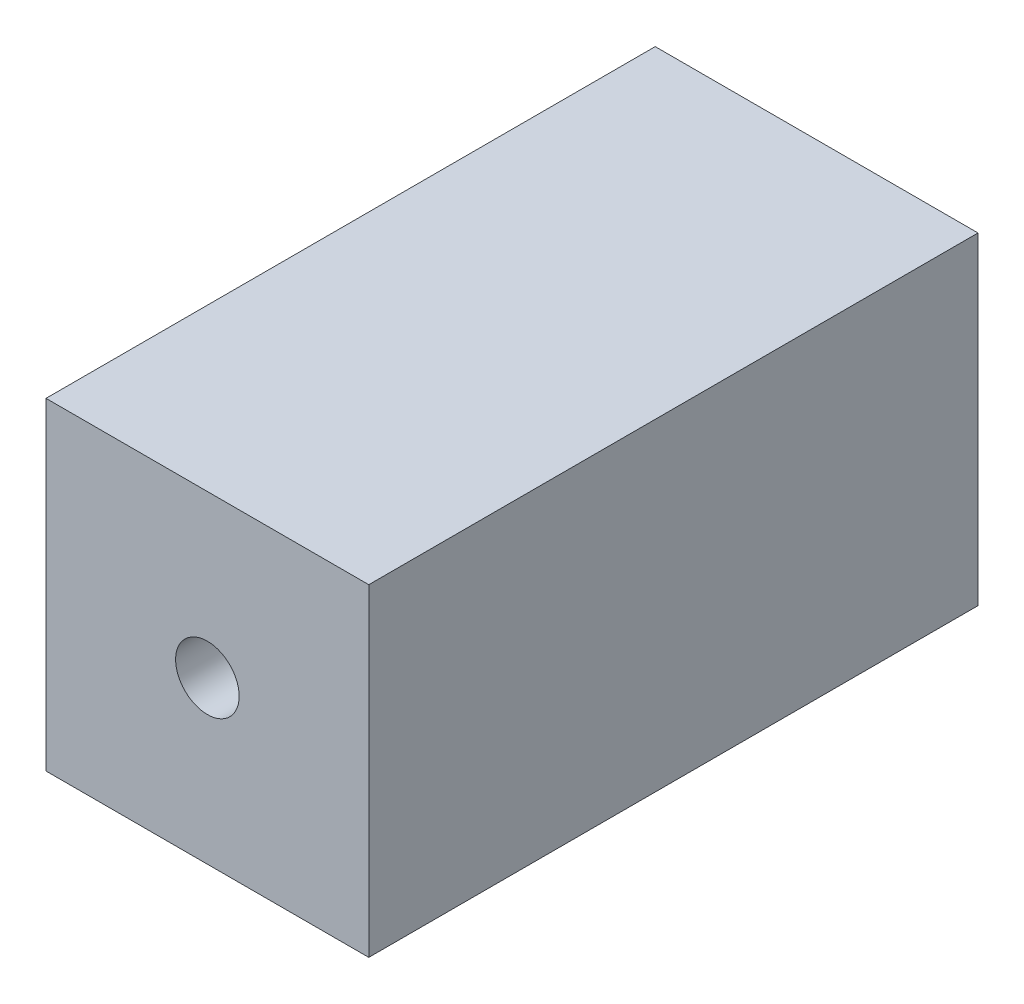
SolidWorks part; units mm, degrees
ref_plane "Front Plane" through (0, 0, 0) normal (0, 0, 1) x (1, 0, 0)
ref_plane "Top Plane" through (0, 0, 0) normal (0, 1, 0) x (1, 0, 0)
ref_plane "Right Plane" through (0, 0, 0) normal (1, 0, 0) x (0, 0, -1)
sketch "Sketch1" plane through (0, 0, 0) normal (0, 0, 1) x (1, 0, 0)
  line L1 (-12.7, -12.7) -> (12.7, -12.7)
  line L2 (-12.7, -12.7) -> (-12.7, 12.7)
  line L3 (-12.7, 12.7) -> (12.7, 12.7)
  line L4 (12.7, -12.7) -> (12.7, 12.7)
  line L5 (-12.7, -12.7) -> (12.7, 12.7) construction
  line L6 (-12.7, 12.7) -> (12.7, -12.7) construction
  point P0 (0, 0)
  dimension "D1" = 25.4
  dimension "D2" = 25.4
extrude "Boss-Extrude1" add sketch "Sketch1" along normal mid plane 47.9406
sketch "Sketch2" plane through (0, 0, 23.9703) normal (0, 0, 1) x (1, 0, 0)
  circle A0 centre (0, 0) radius 2.5
  dimension "D1" = 5
extrude "Cut-Extrude1" cut sketch "Sketch2" against normal through all
